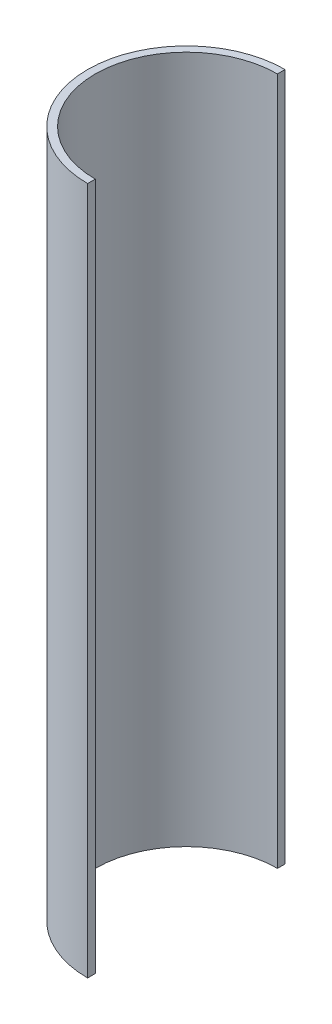
SolidWorks part; units mm, degrees
ref_plane "Front Plane" through (0, 0, 0) normal (0, 0, 1) x (1, 0, 0)
ref_plane "Top Plane" through (0, 0, 0) normal (0, 1, 0) x (1, 0, 0)
ref_plane "Right Plane" through (0, 0, 0) normal (1, 0, 0) x (0, 0, -1)
sketch "Sketch1" plane through (0, 0, 0) normal (0, 1, 0) x (1, 0, 0)
  circle A0 centre (0, 0) radius 38.75
  dimension "D1" = 77.5
extrude "Boss-Extrude2" add sketch "Sketch1" along normal blind 270
sketch "Sketch3" plane through (0, 270, 0) normal (0, 1, 0) x (1, 0, 0)
  line L0 (0, -35.75) -> (0, 35.75)
  arc A2 (0, -35.75) -> (0, 35.75) centre (0, 0) cw
extrude "Cut-Extrude2" cut sketch "Sketch3" against normal blind 480
sketch "Sketch4" plane through (0, 270, 0) normal (0, 1, 0) x (1, 0, 0)
  line L1 (0, 38.75) -> (38.75, 38.75)
  line L2 (0, 38.75) -> (0, -38.75)
  line L3 (0, -38.75) -> (38.75, -38.75)
  line L4 (38.75, 38.75) -> (38.75, -38.75)
  circle A0 centre (0, 0) radius 38.75 construction
extrude "Cut-Extrude3" cut sketch "Sketch4" against normal blind 480
